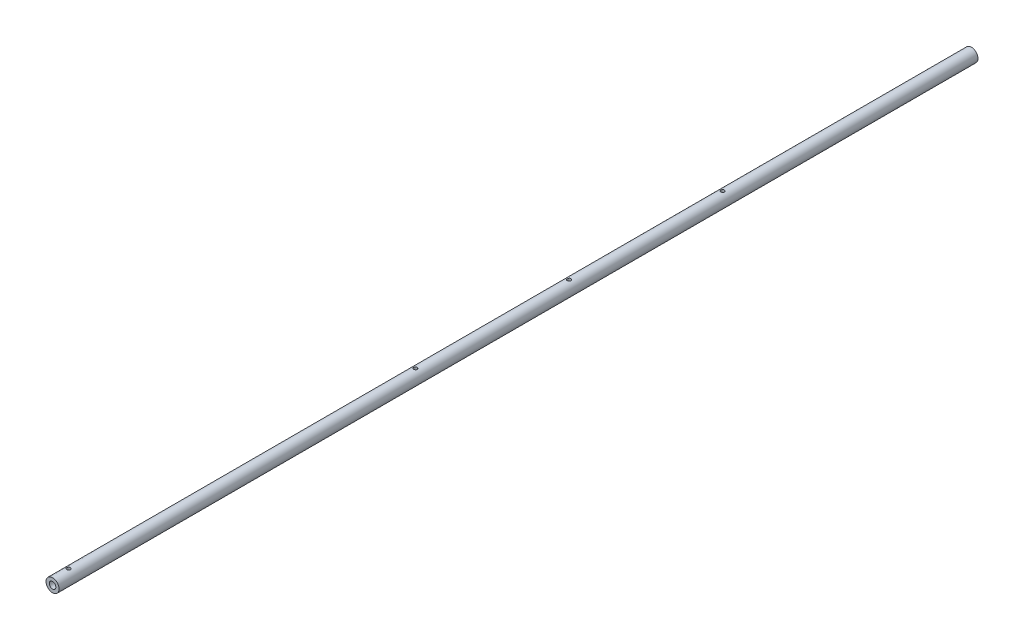
SolidWorks part; units mm, degrees
ref_plane "Front Plane" through (0, 0, 0) normal (0, 0, 1) x (1, 0, 0)
ref_plane "Top Plane" through (0, 0, 0) normal (0, 1, 0) x (1, 0, 0)
ref_plane "Right Plane" through (0, 0, 0) normal (1, 0, 0) x (0, 0, -1)
sketch "Sketch1" plane through (0, 0, 0) normal (0, 0, 1) x (1, 0, 0)
  circle A0 centre (0, 0) radius 3.9306
  circle A1 centre (0, 0) radius 7.8613
  dimension "D1" = 15.7226
  dimension "D2" = 7.8613
extrude "Rod" add sketch "Sketch1" along normal blind 1101.725 contours A0
sketch "Sketch3" plane through (0, 0, 0) normal (0, 1, 0) x (1, 0, 0)
  line L0 (0, -666.75) -> (0, -1076.325) construction
  line L1 (-7.8613, -1101.725) -> (7.8613, -1101.725) construction
  circle A0 centre (0, -298.45) radius 2.1082
  circle A4 centre (0, -482.6) radius 2.1082
  circle A8 centre (0, -666.75) radius 2.1082
  circle A9 centre (0, -1082.675) radius 2.1082
  point P8 (0, 0)
  dimension "D1" = 4.2164
  dimension "D6" = 4.2164
  dimension "D2" = 298.45
  dimension "D4" = 184.15
  dimension "D5" = 409.575
  dimension "D7" = 19.05
  dimension "D3" = 3
extrude "Holes" cut sketch "Sketch3" against normal through all both and the other way through all
ref_plane "Handle Location" through (0, 0, 1076.325) normal (0, 0, 1) x (1, 0, 0)
equation "\"L\"= 43.375"
equation "\"D1@Rod\" = \"L\""
equation "\"N\"= 3"
equation "\"D3@Sketch3\"=\"N\""
equation "\"S\"= 7.25"
equation "\"D4@Sketch3\"=\"S\""
equation "\"O\"= 11.75"
equation "\"D2@Sketch3\"=\"O\""
equation "\"H\"= 16.125"
equation "\"D5@Sketch3\"=\"H\""
